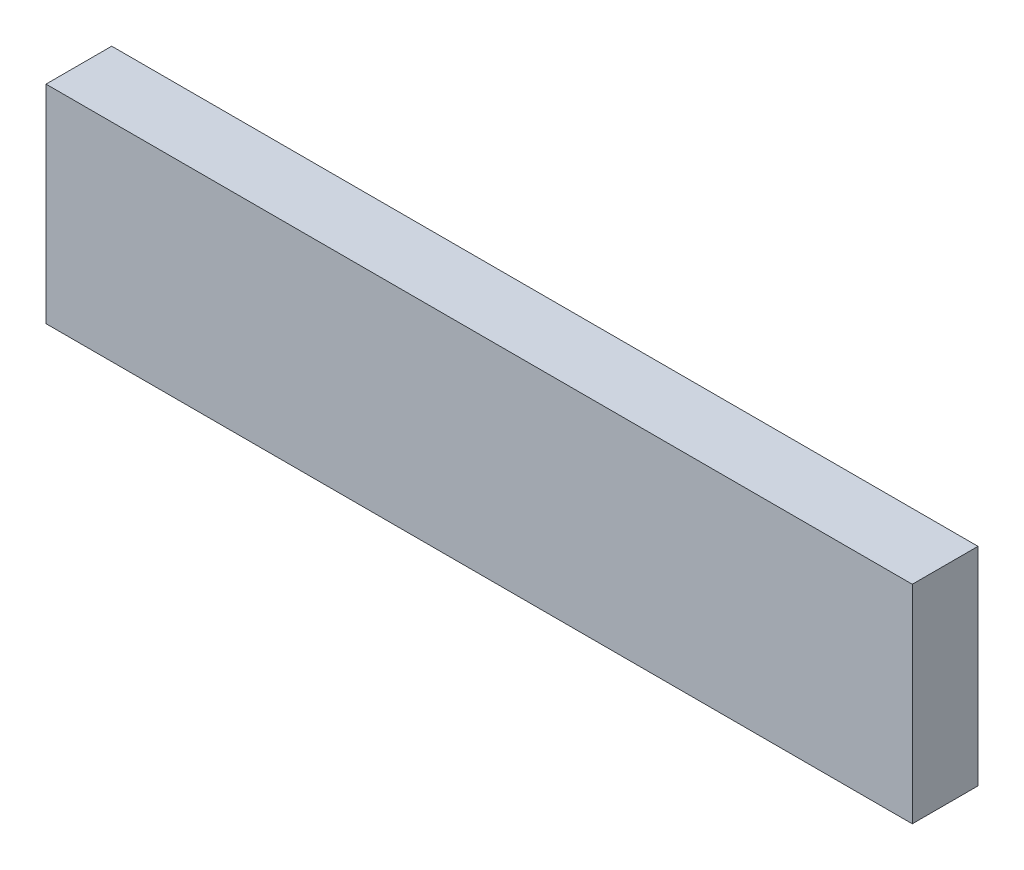
SolidWorks part; units mm, degrees
ref_plane "Front Plane" through (0, 0, 0) normal (0, 0, 1) x (1, 0, 0)
ref_plane "Top Plane" through (0, 0, 0) normal (0, 1, 0) x (1, 0, 0)
ref_plane "Right Plane" through (0, 0, 0) normal (1, 0, 0) x (0, 0, -1)
sketch "Sketch1" plane through (0, 0, 1.3628) normal (-1, 0, 0) x (0, 0, 1)
  line L0 (-1.1728, 0.6) -> (-1.5528, -0.6) construction
  line L1 (-1.5528, 0.6) -> (-1.1728, 0.6)
  line L2 (-1.5528, 0.6) -> (-1.5528, -0.6)
  line L3 (-1.5528, -0.6) -> (-1.1728, -0.6)
  line L4 (-1.1728, 0.6) -> (-1.1728, -0.6)
  line L5 (-1.5528, 0.6) -> (-1.1728, -0.6) construction
  point P4 (-1.3628, 0)
  dimension "D1" = 0.38
  dimension "D2" = 1.2
extrude "Boss-Extrude1" add sketch "Sketch1" along normal mid plane 5.01
